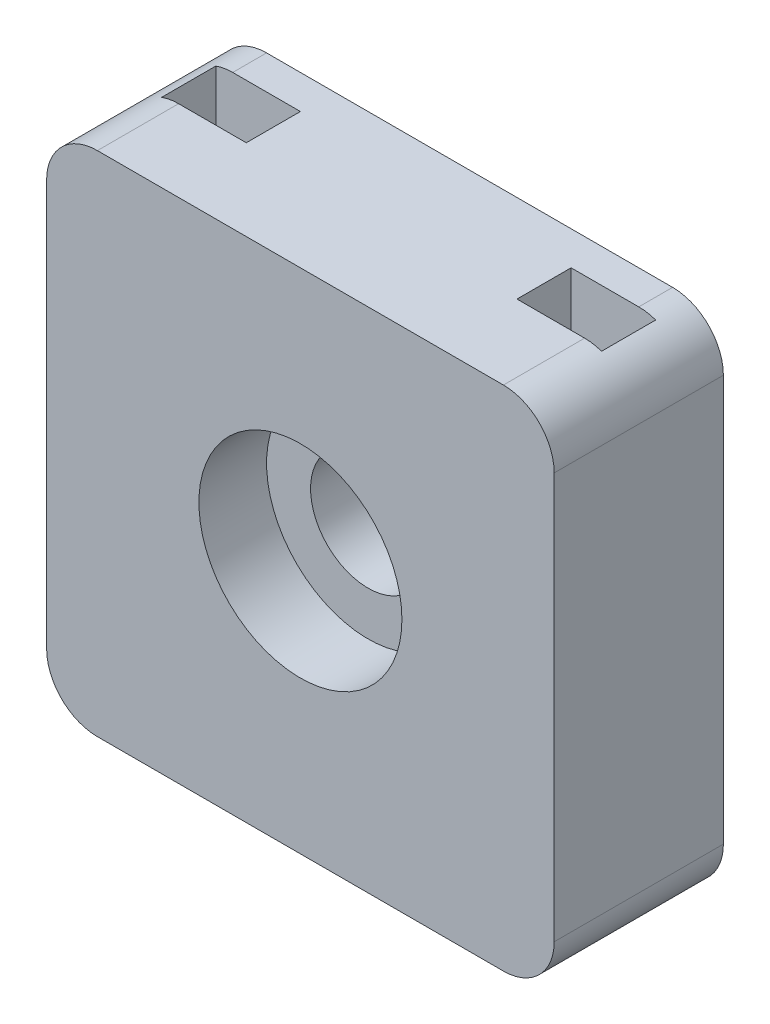
SolidWorks part; units mm, degrees
material "Nailon 101"
ref_plane "Alzado" through (0, 0, 0) normal (0, 0, 1) x (1, 0, 0)
ref_plane "Planta" through (0, 0, 0) normal (0, 1, 0) x (1, 0, 0)
ref_plane "Vista lateral" through (0, 0, 0) normal (1, 0, 0) x (0, 0, -1)
sketch "Croquis1" plane through (0, 0, 0) normal (0, 0, 1) x (1, 0, 0)
  line L0 (-6, -7.5) -> (6, -7.5)
  line L1 (7.5, -6) -> (7.5, 6)
  line L2 (6, 7.5) -> (-6, 7.5)
  line L3 (-7.5, 6) -> (-7.5, -6)
  arc A0 (6, -7.5) -> (7.5, -6) centre (6, -6) ccw
  arc A1 (7.5, 6) -> (6, 7.5) centre (6, 6) ccw
  arc A2 (-6, 7.5) -> (-7.5, 6) centre (-6, 6) ccw
  arc A3 (-7.5, -6) -> (-6, -7.5) centre (-6, -6) ccw
  dimension "D1" = 1.5
  dimension "D2" = 1.5
  dimension "D3" = 1.5
  dimension "D4" = 1.5
  dimension "D5" = 6
  dimension "D6" = 7.5
  dimension "D7" = 6
  dimension "D8" = 7.5
  dimension "D9" = 7.5
  dimension "D10" = 6
  dimension "D11" = 7.5
  dimension "D12" = 6
  dimension "D13" = 6
  dimension "D14" = 7.5
  dimension "D15" = 6
  dimension "D16" = 7.5
  dimension "D17" = 7.5
  dimension "D18" = 6
  dimension "D19" = 7.5
  dimension "D20" = 6
extrude "Base_15x15" add sketch "Croquis1" along normal blind 5
sketch "Croquis2" plane through (0, 0, 0) normal (0, 0, 1) x (1, 0, 0)
  circle A0 centre (0, 0) radius 1.7
  dimension "D1" = 3.4
extrude "Paso_M3" cut sketch "Croquis2" along normal blind 5
sketch "Croquis3" plane through (0, 0, 0) normal (0, 0, 1) x (1, 0, 0)
  circle A0 centre (0, 0) radius 3
  dimension "D1" = 6
extrude "Caja_cabeza" cut sketch "Croquis3" along normal blind 2 from offset 3
sketch "Croquis4" plane through (0, 0, 0) normal (1, 0, 0) x (0, 0, -1)
  line L0 (-1, -8) -> (-1, 8)
  line L1 (-1, 8) -> (-2.6, 8)
  line L2 (-2.6, 8) -> (-2.6, -8)
  line L3 (-2.6, -8) -> (-1, -8)
  dimension "D1" = 1
  dimension "D2" = 8
  dimension "D3" = 1
  dimension "D4" = 8
  dimension "D5" = 2.6
  dimension "D6" = 8
  dimension "D7" = 2.6
  dimension "D8" = 8
extrude "Tunel_cincho_A" cut sketch "Croquis4" along normal blind 2.5 from offset 4
sketch "Croquis5" plane through (0, 0, 0) normal (1, 0, 0) x (0, 0, -1)
  line L0 (-1, -8) -> (-1, 8)
  line L1 (-1, 8) -> (-2.6, 8)
  line L2 (-2.6, 8) -> (-2.6, -8)
  line L3 (-2.6, -8) -> (-1, -8)
  dimension "D1" = 1
  dimension "D2" = 8
  dimension "D3" = 1
  dimension "D4" = 8
  dimension "D5" = 2.6
  dimension "D6" = 8
  dimension "D7" = 2.6
  dimension "D8" = 8
extrude "Tunel_cincho_B" cut sketch "Croquis5" along normal blind 2.5 from offset 6.5
